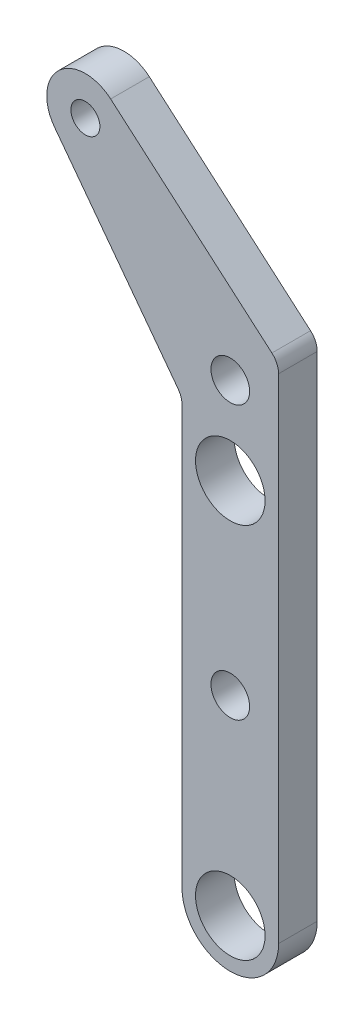
SolidWorks part; units mm, degrees
material "Thornel Mat VMA"
ref_plane "前视基准面" through (0, 0, 0) normal (0, 0, 1) x (1, 0, 0)
ref_plane "上视基准面" through (0, 0, 0) normal (0, 1, 0) x (1, 0, 0)
ref_plane "右视基准面" through (0, 0, 0) normal (1, 0, 0) x (0, 0, -1)
sketch "草图1" plane through (0, 0, 0) normal (0, 0, 1) x (1, 0, 0)
  line L0 (-63.6974, 1.3001) -> (-160.5974, 1.3001) construction
  line L1 (-188.3974, -74.6999) -> (-196.8974, -74.6999) construction
  line L3 (-188.3974, 77.3001) -> (-188.3974, -74.6999) construction
  line L5 (-160.5974, 77.3001) -> (-160.5974, -74.6999) construction
  line L6 (-152.0974, 77.3001) -> (-160.5974, 77.3001) construction
  line L7 (-152.0974, 77.3001) -> (-152.0974, -74.6999) construction
  line L8 (-152.0974, -74.6999) -> (-160.5974, -74.6999) construction
  line L9 (-196.8974, 77.3001) -> (-196.8974, -74.6999) construction
  line L10 (-188.3974, 77.3001) -> (-196.8974, 77.3001) construction
  line L11 (55, 0) -> (-55, 0) construction
  line L12 (-146.0974, 20.8001) -> (-146.0974, -18.1999)
  line L13 (-63.6974, 22.3001) -> (-134.7974, 22.3001) construction
  line L14 (-63.6974, 22.3001) -> (-63.6974, -19.6999) construction
  line L15 (-63.6974, -19.6999) -> (-134.7974, -19.6999) construction
  line L16 (-134.7974, 22.3001) -> (-134.7974, -19.6999) construction
  line L17 (-146.0974, 20.8001) -> (-60, 39)
  line L18 (-146.0974, -18.1999) -> (-60, 0)
  line L19 (-60, 0) -> (-60, 39)
  line L20 (-124.0083, -11.4863) -> (-75, 64)
  line L21 (-138, 106.5) -> (-138, 78.0686) construction
  line L22 (-75, 64) -> (27.8173, 64) construction
  line L23 (-123.5947, -13.4431) -> (-124.0083, -11.4863) construction
  circle A0 centre (-60, 0) radius 5 construction
  circle A1 centre (-60, 0) radius 3
  point P14 (-146.0974, 1.3001)
  dimension "D12" = 10
  dimension "D15" = 5
  dimension "D21" = 6
  dimension "D1" = 96.9
  dimension "D2" = 27.8
  dimension "D3" = 44.8
  dimension "D4" = 152
  dimension "D5" = 88
  dimension "D6" = 42
  dimension "D7" = 71.1
  dimension "D8" = 39
  dimension "D9" = 11.3
  dimension "D10" = 110
  dimension "D11" = 15
  dimension "D13" = 23
  dimension "D14" = 2
  dimension "D16" = 1.3001
  dimension "D17" = 138
  dimension "D18" = 64
  dimension "D20" = 90
sketch "草图2" plane through (0, 0, 0) normal (0, 0, 1) x (1, 0, 0)
  line L0 (-60, 19.75) -> (-60, 0) construction
  line L1 (-65, 0) -> (-65, 44)
  line L7 (-55, 52) -> (-55, 0)
  line L8 (-78.2, 61.6) -> (-65, 44)
  line L9 (-72.3843, 67.0262) -> (-55, 52)
  circle A0 centre (-60, 0) radius 5 construction
  arc A1 (-65, 0) -> (-55, 0) centre (-60, 0) ccw
  circle A3 centre (-60, 39) radius 3.6
  circle A4 centre (-60, 0) radius 3.6
  circle A5 centre (-75, 64) radius 1.5
  arc A6 (-72.3843, 67.0262) -> (-78.2, 61.6) centre (-75, 64) ccw
  circle A8 centre (-60, 19.75) radius 2
  circle A9 centre (-60, 48) radius 2
  point P3 (-55, 0)
  dimension "D1" = 3
  dimension "D2" = 7.2
  dimension "D3" = 52
  dimension "D6" = 4
  dimension "D4" = 44
  dimension "D10" = 4
  dimension "D12" = 9
  dimension "D11" = 19.75
extrude "凸台-拉伸1" add sketch "草图2" along normal blind 4
fillet "圆角1" radius 2 2 edges at (-55, 52, 2) (-65, 44, 2)
